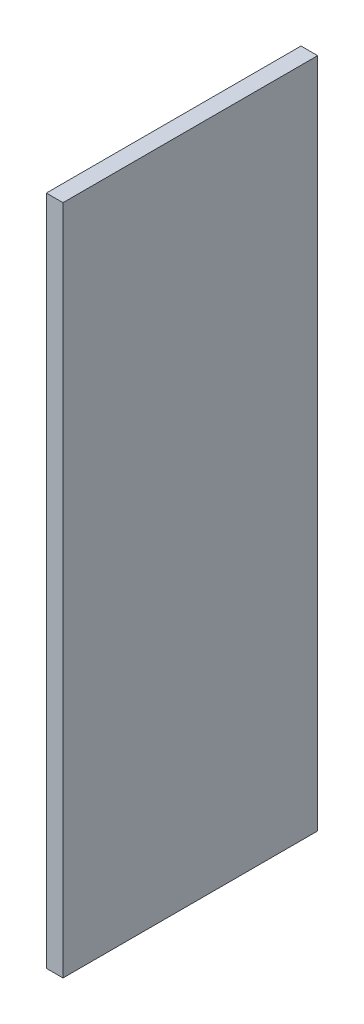
SolidWorks part; units mm, degrees
ref_plane "Front" through (0, 0, 0) normal (0, 0, 1) x (1, 0, 0)
ref_plane "Top" through (0, 0, 0) normal (0, 1, 0) x (1, 0, 0)
ref_plane "Right" through (0, 0, 0) normal (1, 0, 0) x (0, 0, -1)
sketch "Sketch1" plane through (0, 0, 0) normal (1, 0, 0) x (0, 0, -1)
  line L1 (139.7, -368.3) -> (-139.7, -368.3)
  line L2 (139.7, -368.3) -> (139.7, 368.3)
  line L3 (139.7, 368.3) -> (-139.7, 368.3)
  line L4 (-139.7, -368.3) -> (-139.7, 368.3)
  line L5 (139.7, -368.3) -> (-139.7, 368.3) construction
  line L6 (139.7, 368.3) -> (-139.7, -368.3) construction
  point P0 (0, 0)
  dimension "D1" = 279.4
  dimension "D2" = 736.6
extrude "Boss-Extrude1" add sketch "Sketch1" along normal blind 18.288
